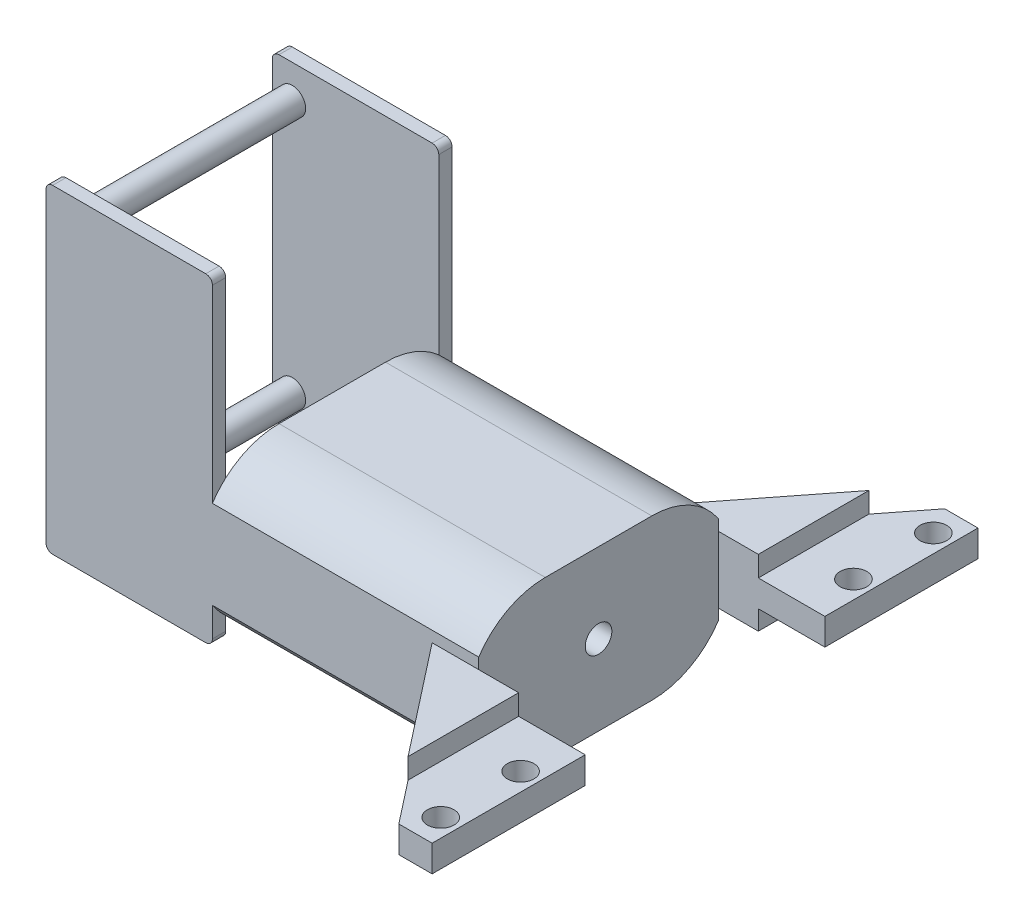
SolidWorks part; units mm, degrees
ref_plane "Plan de face" through (0, 0, 0) normal (0, 0, 1) x (1, 0, 0)
ref_plane "Plan de dessus" through (0, 0, 0) normal (0, 1, 0) x (1, 0, 0)
ref_plane "Plan de droite" through (0, 0, 0) normal (1, 0, 0) x (0, 0, -1)
sketch "Esquisse1" plane through (0, 0, 0) normal (0, 0, 1) x (1, 0, 0)
  line L1 (0, 0) -> (25, 0)
  line L2 (0, 0) -> (0, 48)
  line L3 (0, 48) -> (25, 48)
  line L4 (25, 0) -> (25, 48)
  dimension "D1" = 25
  dimension "D2" = 48
extrude "Boss.-Extru.1" add sketch "Esquisse1" along normal blind 2
sketch "Esquisse2" plane through (0, 0, 0) normal (0, 0, -1) x (-1, 0, 0)
  line L0 (0, 48) -> (0, 0) construction
  line L1 (-25, 48) -> (0, 48) construction
  line L2 (0, 0) -> (-25, 0) construction
  circle A0 centre (-3, 5) radius 2
  circle A1 centre (-3, 43) radius 2
  dimension "D3" = 4
  dimension "D4" = 0
  dimension "D6" = 4
  dimension "D1" = 3
  dimension "D2" = 5
  dimension "D5" = 5
extrude "Boss.-Extru.2" add sketch "Esquisse2" along normal blind 32
sketch "Esquisse3" plane through (0, 0, -32) normal (0, 0, -1) x (-1, 0, 0)
  line L0 (-25, 48) -> (0, 48) construction
  line L1 (0, 48) -> (-25, 48)
  line L2 (0, 48) -> (0, 0)
  line L3 (0, 0) -> (-25, 0)
  line L4 (-25, 48) -> (-25, 0)
  line L5 (-25, 0) -> (-25, 48) construction
  line L6 (0, 48) -> (0, 0) construction
  line L7 (0, 0) -> (-25, 0) construction
  dimension "D1" = 0
  dimension "D2" = 0
  dimension "D3" = 0
  dimension "D4" = 0
extrude "Boss.-Extru.3" add sketch "Esquisse3" along normal blind 2
sketch "Esquisse5" plane through (25, 0, 0) normal (1, 0, 0) x (0, 0, -1)
  line L0 (-2, 0) -> (-2, 48) construction
  line L1 (-2, 0) -> (34, 0)
  line L2 (-2, 0) -> (-2, 24)
  line L3 (-2, 24) -> (34, 24)
  line L4 (34, 0) -> (34, 24)
  line L5 (34, 48) -> (34, 0) construction
  line L6 (-2, 0) -> (0, 0) construction
  dimension "D1" = 0
  dimension "D2" = 24
extrude "Boss.-Extru.4" add sketch "Esquisse5" along normal blind 40
sketch "Esquisse6" plane through (65, 0, 0) normal (1, 0, 0) x (0, 0, -1)
  line L0 (34, 24) -> (-2, 24) construction
  line L2 (34, 0) -> (34, 24) construction
  circle A0 centre (16, 12) radius 2
  dimension "D1" = 4
  dimension "D2" = 12
  dimension "D3" = 18
extrude "Enlèv. mat.-Extru.1" cut sketch "Esquisse6" against normal blind 10
sketch "Esquisse7" plane through (65, 0, 0) normal (1, 0, 0) x (0, 0, -1)
  line L0 (-2, 0) -> (34, 0) construction
  line L1 (8, 24) -> (8, 33.4992)
  line L2 (8, 33.4992) -> (-16.8749, 33.4992)
  line L3 (-16.8749, 33.4992) -> (-16.8749, 0)
  line L4 (-16.8749, 0) -> (8, 0)
  line L5 (34, 24) -> (-2, 24) construction
  line L6 (-2, 24) -> (-2, 0) construction
  line L7 (24, 24) -> (24, 33.4992)
  line L8 (24, 33.4992) -> (42.8284, 33.4992)
  line L9 (42.8284, 33.4992) -> (42.8284, 0)
  line L10 (42.8284, 0) -> (24, 0)
  line L11 (34, 0) -> (34, 24) construction
  arc A0 (8, 0) -> (8, 24) centre (8, 12) cw
  arc A1 (24, 24) -> (24, 0) centre (24, 12) cw
  dimension "D1" = 0
  dimension "D2" = 10
  dimension "D3" = 10
  dimension "D4" = 10
extrude "Enlèv. mat.-Extru.2" cut sketch "Esquisse7" against normal blind 40
sketch "Esquisse9" plane through (0, 0, 2) normal (0, 0, 1) x (1, 0, 0)
  line L0 (65, 18.6332) -> (65, 5.3668) construction
  line L1 (58, 17) -> (81, 17)
  line L2 (58, 17) -> (58, 7)
  line L3 (58, 7) -> (81, 7)
  line L4 (81, 17) -> (81, 7)
  line L5 (25, 0) -> (65, 0) construction
  line L6 (25, 24) -> (65, 24) construction
  dimension "D1" = 7
  dimension "D2" = 7
  dimension "D3" = 7
  dimension "D4" = 23
extrude "Boss.-Extru.5" add sketch "Esquisse9" along normal blind 23
sketch "Esquisse10" plane through (0, 17, 0) normal (0, 1, 0) x (1, 0, 0)
  circle A0 centre (78.293, -21) radius 2
  circle A1 centre (78.293, -9) radius 2
  dimension "D1" = 4
  dimension "D2" = 4
  dimension "D3" = 7
  dimension "D4" = 12
extrude "Enlèv. mat.-Extru.3" cut sketch "Esquisse10" against normal blind 23
sketch "Esquisse11" plane through (0, 0, -34) normal (0, 0, -1) x (-1, 0, 0)
  line L0 (-81, 17) -> (-65, 17) construction
  line L1 (-58, 7) -> (-81, 7)
  line L2 (-58, 7) -> (-58, 17)
  line L3 (-58, 17) -> (-81, 17)
  line L4 (-81, 7) -> (-81, 17)
  line L5 (-65, 7) -> (-81, 7) construction
  line L6 (-81, 7) -> (-81, 17) construction
  dimension "D1" = 0
  dimension "D2" = 0
  dimension "D3" = 0
  dimension "D4" = 0
extrude "Boss.-Extru.6" add sketch "Esquisse11" along normal blind 23
sketch "Esquisse13" plane through (0, 17, 0) normal (0, 1, 0) x (1, 0, 0)
  line L0 (65, 34) -> (81, 34) construction
  circle A0 centre (78.293, 41) radius 2
  circle A1 centre (78.293, 53) radius 2
  circle A3 centre (78.293, -9) radius 2 construction
  dimension "D1" = 4
  dimension "D2" = 4
  dimension "D3" = 0
  dimension "D4" = 12
  dimension "D5" = 7
  dimension "D6" = 0
extrude "Enlèv. mat.-Extru.4" cut sketch "Esquisse13" against normal blind 23
sketch "Esquisse14" plane through (0, 17, 0) normal (0, 1, 0) x (1, 0, 0)
  line L0 (58, 34) -> (76, 57)
  line L1 (58, 57) -> (81, 57) construction
  line L2 (76, 57) -> (58, 57)
  line L3 (58, 57) -> (58, 34)
  line L4 (58, -2) -> (76, -25)
  line L5 (81, -25) -> (58, -25) construction
  line L6 (76, -25) -> (58, -25)
  line L7 (58, -25) -> (58, -2)
  dimension "D1" = 5
extrude "Enlèv. mat.-Extru.5" cut sketch "Esquisse14" against normal blind 23
sketch "Esquisse15" plane through (81, 0, 0) normal (1, 0, 0) x (0, 0, -1)
  line L0 (57, 17) -> (57, 7) construction
  line L1 (-25, 17) -> (57, 17)
  line L2 (-25, 17) -> (-25, 13.9252)
  line L3 (-25, 13.9252) -> (57, 13.9252)
  line L4 (57, 17) -> (57, 13.9252)
  line L5 (-25, 7) -> (-25, 17) construction
  line L6 (57, 7) -> (-25, 7)
  line L7 (57, 7) -> (57, 9.9252)
  line L8 (57, 9.9252) -> (-25, 9.9252)
  line L9 (-25, 7) -> (-25, 9.9252)
  dimension "D1" = 4
extrude "Enlèv. mat.-Extru.6" cut sketch "Esquisse15" against normal blind 10
fillet "Congé1" radius 1 4 edges at (25, 0, 1) (0, 48, 1) (25, 48, 1) (0, 0, 1)
fillet "Congé2" radius 1 4 edges at (0, 0, -33) (0, 48, -33) (25, 48, -33) (25, 0, -33)
